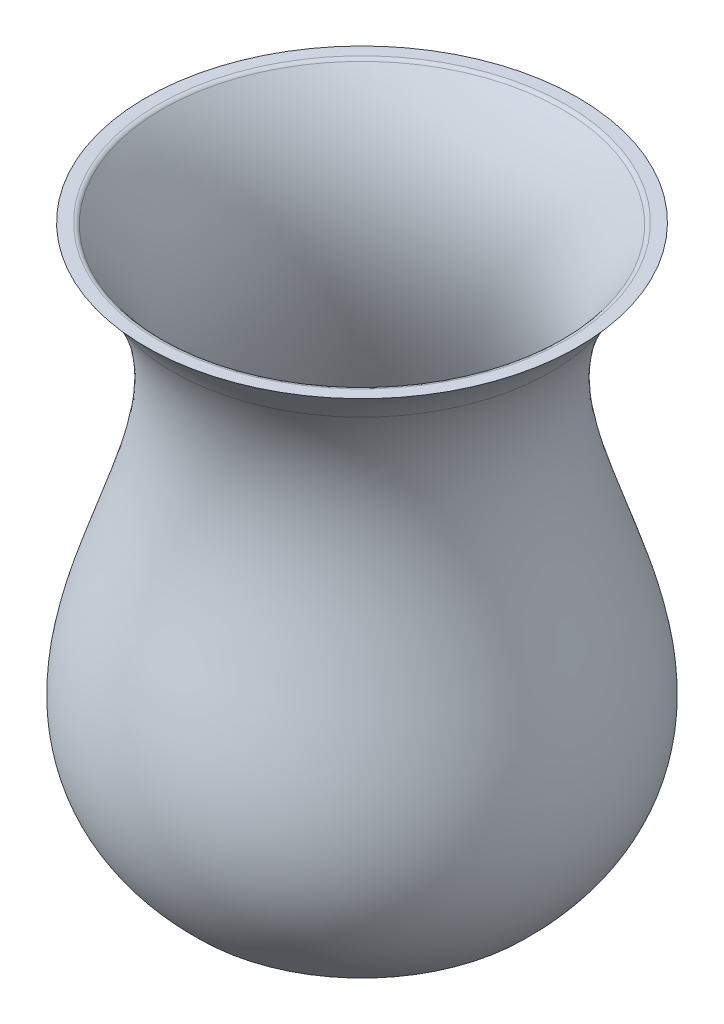
SolidWorks part; units mm, degrees
other "Markup1"
sketch "Sketch2" plane through (-46.815, 100, 46.815) normal (-0.8425, 0.3723, 0.3893) x (0.4224, 0.0081, 0.9064)
material "A-Glass Fiber"
ref_plane "Front Plane" through (0, 0, 0) normal (0, 0, 1) x (1, 0, 0)
ref_plane "Top Plane" through (0, 0, 0) normal (0, 1, 0) x (1, 0, 0)
ref_plane "Right Plane" through (0, 0, 0) normal (1, 0, 0) x (0, 0, -1)
sketch "Sketch1" plane through (0, 0, 0) normal (0, 0, 1) x (1, 0, 0)
  line L0 (0, 0) -> (0, 100) construction
  line L1 (40, 100) -> (0, 100)
  line L2 (30, 0) -> (0, 0)
  line L3 (0, 0) -> (0, 100)
  spline S0 degree 3 poles (40, 100) (8.2143, 65.6764) (63.63, 31.7032) (30, 0) knots 0 0 0 0 1 1 1 1
  point P5 (39.3527, 25.1992)
  point P7 (34.8254, 50.6218)
  point P9 (0, 85.0989)
  point P10 (-17.4127, 134.8993)
  point P11 (0, 0)
  point P12 (0, 0)
  point P13 (0, 0)
  point P14 (44.2283, 24.8509)
  point P15 (41.4422, 35.6468)
  point P16 (38.6562, 44.3532)
  point P17 (53.2829, 19.6271)
  point P18 (41.7905, 50.2735)
  point P19 (60.248, 18.9306)
  point P20 (46.6661, 54.8008)
  point P21 (0, 0)
  point P22 (0, 0)
  point P23 (0, 0)
  point P24 (49.8003, 48.8805)
  point P25 (48.0591, 45.0497)
  point P26 (45.9695, 51.6665)
  point P27 (56.4172, 31.4678)
  point P28 (45.273, 59.6764)
  point P29 (46.6661, 51.3183)
  point P30 (51.1934, 43.3084)
  point P31 (59.2032, 22.7614)
  point P32 (40.6262, 50.0915)
  point P33 (49.122, 20.6691)
  point P34 (32.7756, 45.6975)
  point P35 (39.6736, 16.8507)
  point P36 (39.632, 19.0324)
  point P37 (32.5258, 58.7877)
  point P38 (41.0355, 28.638)
  dimension "D1" = 100
  dimension "D2" = 40
  dimension "D3" = 30
revolve "Revolve2" add sketch "Sketch1" angle 360 about L0
shell "Shell26" thickness 2
fillet "Fillet1" radius 1 2 edges at (0, 2, -29.1966) (0, 100, -37.3174)
ref_plane "Plane1" through (0, 93.4587, 0) normal (0, 1, 0) x (1, 0, 0)
split line "Split Line17"
